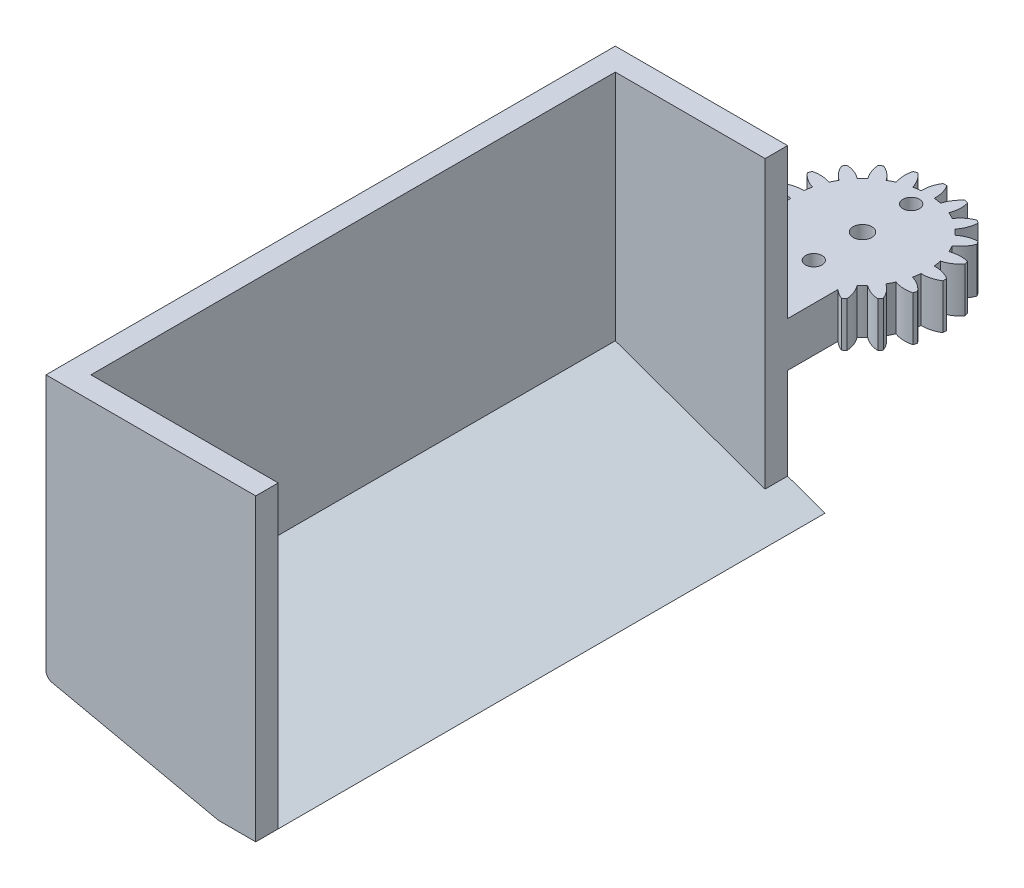
SolidWorks part; units mm, degrees
ref_plane "前视基准面" through (0, 0, 0) normal (0, 0, 1) x (1, 0, 0)
ref_plane "上视基准面" through (0, 0, 0) normal (0, 1, 0) x (1, 0, 0)
ref_plane "右视基准面" through (0, 0, 0) normal (1, 0, 0) x (0, 0, -1)
sketch "草图1" plane through (0, 0, 0) normal (0, 1, 0) x (1, 0, 0)
  line L0 (-5, 0) -> (5, 0) construction
  line L1 (5, 0) -> (5, -18)
  line L2 (-5, 0) -> (-5, -15)
  line L3 (-5, -15) -> (-18, -15)
  line L4 (-18, -15) -> (-18, -91)
  line L5 (-18, -91) -> (10, -91)
  line L6 (10, -91) -> (10, -88)
  line L7 (10, -88) -> (-15, -88)
  line L8 (-15, -88) -> (-15, -18)
  line L9 (-15, -18) -> (5, -18)
  arc A0 (5, 0) -> (-5, 0) centre (0, 0) ccw
  arc A1 (-5, 0) -> (5, 0) centre (0, 0) ccw construction
  circle A2 centre (0, 0) radius 1.25
  dimension "D1" = 10
  dimension "D2" = 3
  dimension "D3" = 3
  dimension "D4" = 3
  dimension "D5" = 10
  dimension "D6" = 15
  dimension "D7" = 25
  dimension "D8" = 70
extrude "凸台-拉伸1" add sketch "草图1" against normal blind 6
sketch "草图2" plane through (0, 0, 0) normal (0, 1, 0) x (1, 0, 0)
  line L0 (-15, -18) -> (5, -18) construction
  line L1 (-15, -88) -> (-15, -18) construction
  line L2 (10, -88) -> (-15, -88) construction
  line L3 (10, -91) -> (10, -88) construction
  line L4 (-18, -91) -> (10, -91) construction
  line L5 (-18, -15) -> (-18, -91) construction
  line L6 (-15, -18) -> (5, -18)
  line L7 (-15, -88) -> (-15, -18)
  line L8 (10, -88) -> (-15, -88)
  line L9 (10, -91) -> (10, -88)
  line L10 (-18, -91) -> (10, -91)
  line L11 (-18, -15) -> (-18, -91)
  line L12 (-18, -15) -> (5, -15)
  line L13 (5, -18) -> (5, 0) construction
  line L14 (5, -15) -> (5, -18)
extrude "凸台-拉伸2" add sketch "草图2" along normal mid plane 40
sketch "草图4" plane through (0, -6, 0) normal (0, -1, 0) x (1, 0, 0)
  circle A0 centre (0, 0) radius 1.25
  arc A80 (0.8607, 8.7066) -> (0.2434, 10.9973) centre (-3.1365, 8.858) ccw
  arc A81 (0.2434, 10.9973) -> (-0.2736, 10.9966) centre (0, 0) ccw
  arc A82 (-0.2736, 10.9966) -> (-0.8846, 8.7042) centre (3.1121, 8.8666) ccw
  arc A83 (-0.8846, 8.7042) -> (-1.8719, 8.5464) centre (0, 0) ccw
  arc A84 (-1.8719, 8.5464) -> (-3.1668, 10.5343) centre (-5.7202, 7.4553) ccw
  arc A85 (-3.1668, 10.5343) -> (-3.6584, 10.3738) centre (0, 0) ccw
  arc A86 (-3.6584, 10.3738) -> (-3.531, 8.0048) centre (0.2198, 9.3944) ccw
  arc A87 (-3.531, 8.0048) -> (-4.4213, 7.5497) centre (0, 0) ccw
  arc A88 (-4.4213, 7.5497) -> (-6.2671, 9.0401) centre (-7.7441, 5.3227) ccw
  arc A89 (-6.2671, 9.0401) -> (-6.685, 8.7356) centre (0, 0) ccw
  arc A90 (-6.685, 8.7356) -> (-5.8318, 6.5219) centre (-2.6939, 9.0025) ccw
  arc A91 (-5.8318, 6.5219) -> (-6.5379, 5.8139) centre (0, 0) ccw
  arc A92 (-6.5379, 5.8139) -> (-8.7539, 6.661) centre (-9.0099, 2.6692) ccw
  arc A93 (-8.7539, 6.661) -> (-9.0573, 6.2423) centre (0, 0) ccw
  arc A94 (-9.0573, 6.2423) -> (-7.5618, 4.4005) centre (-5.344, 7.7294) ccw
  arc A95 (-7.5618, 4.4005) -> (-8.0145, 3.509) centre (0, 0) ccw
  arc A96 (-8.0145, 3.509) -> (-10.3838, 3.6299) centre (-9.3937, -0.2457) ccw
  arc A97 (-10.3838, 3.6299) -> (-10.5429, 3.1379) centre (0, 0) ccw
  arc A98 (-10.5429, 3.1379) -> (-8.5515, 1.8484) centre (-7.471, 5.6997) ccw
  arc A99 (-8.5515, 1.8484) -> (-8.7066, 0.8607) centre (0, 0) ccw
  arc A100 (-8.7066, 0.8607) -> (-10.9973, 0.2434) centre (-8.858, -3.1365) ccw
  arc A101 (-10.9973, 0.2434) -> (-10.9966, -0.2736) centre (0, 0) ccw
  arc A102 (-10.9966, -0.2736) -> (-8.7042, -0.8846) centre (-8.8666, 3.1121) ccw
  arc A103 (-8.7042, -0.8846) -> (-8.5464, -1.8719) centre (0, 0) ccw
  arc A104 (-8.5464, -1.8719) -> (-10.5343, -3.1668) centre (-7.4553, -5.7202) ccw
  arc A105 (-10.5343, -3.1668) -> (-10.3738, -3.6584) centre (0, 0) ccw
  arc A106 (-10.3738, -3.6584) -> (-8.0048, -3.531) centre (-9.3944, 0.2198) ccw
  arc A107 (-8.0048, -3.531) -> (-7.5497, -4.4213) centre (0, 0) ccw
  arc A108 (-7.5497, -4.4213) -> (-9.0401, -6.2671) centre (-5.3227, -7.7441) ccw
  arc A109 (-9.0401, -6.2671) -> (-8.7356, -6.685) centre (0, 0) ccw
  arc A110 (-8.7356, -6.685) -> (-6.5219, -5.8318) centre (-9.0025, -2.6939) ccw
  arc A111 (-6.5219, -5.8318) -> (-5.8139, -6.5379) centre (0, 0) ccw
  arc A112 (-5.8139, -6.5379) -> (-6.661, -8.7539) centre (-2.6692, -9.0099) ccw
  arc A113 (-6.661, -8.7539) -> (-6.2423, -9.0573) centre (0, 0) ccw
  arc A114 (-6.2423, -9.0573) -> (-4.4005, -7.5618) centre (-7.7294, -5.344) ccw
  arc A115 (-4.4005, -7.5618) -> (-3.509, -8.0145) centre (0, 0) ccw
  arc A116 (-3.509, -8.0145) -> (-3.6299, -10.3838) centre (0.2457, -9.3937) ccw
  arc A117 (-3.6299, -10.3838) -> (-3.1379, -10.5429) centre (0, 0) ccw
  arc A118 (-3.1379, -10.5429) -> (-1.8484, -8.5515) centre (-5.6997, -7.471) ccw
  arc A119 (-1.8484, -8.5515) -> (-0.8607, -8.7066) centre (0, 0) ccw
  arc A120 (-0.8607, -8.7066) -> (-0.2434, -10.9973) centre (3.1365, -8.858) ccw
  arc A121 (-0.2434, -10.9973) -> (0.2736, -10.9966) centre (0, 0) ccw
  arc A122 (0.2736, -10.9966) -> (0.8846, -8.7042) centre (-3.1121, -8.8666) ccw
  arc A123 (0.8846, -8.7042) -> (1.8719, -8.5464) centre (0, 0) ccw
  arc A124 (1.8719, -8.5464) -> (3.1668, -10.5343) centre (5.7202, -7.4553) ccw
  arc A125 (3.1668, -10.5343) -> (3.6584, -10.3738) centre (0, 0) ccw
  arc A126 (3.6584, -10.3738) -> (3.531, -8.0048) centre (-0.2198, -9.3944) ccw
  arc A127 (3.531, -8.0048) -> (4.4213, -7.5497) centre (0, 0) ccw
  arc A128 (4.4213, -7.5497) -> (6.2671, -9.0401) centre (7.7441, -5.3227) ccw
  arc A129 (6.2671, -9.0401) -> (6.685, -8.7356) centre (0, 0) ccw
  arc A130 (6.685, -8.7356) -> (5.8318, -6.5219) centre (2.6939, -9.0025) ccw
  arc A131 (5.8318, -6.5219) -> (6.5379, -5.8139) centre (0, 0) ccw
  arc A132 (6.5379, -5.8139) -> (8.7539, -6.661) centre (9.0099, -2.6692) ccw
  arc A133 (8.7539, -6.661) -> (9.0573, -6.2423) centre (0, 0) ccw
  arc A134 (9.0573, -6.2423) -> (7.5618, -4.4005) centre (5.344, -7.7294) ccw
  arc A135 (7.5618, -4.4005) -> (8.0145, -3.509) centre (0, 0) ccw
  arc A136 (8.0145, -3.509) -> (10.3838, -3.6299) centre (9.3937, 0.2457) ccw
  arc A137 (10.3838, -3.6299) -> (10.5429, -3.1379) centre (0, 0) ccw
  arc A138 (10.5429, -3.1379) -> (8.5515, -1.8484) centre (7.471, -5.6997) ccw
  arc A139 (8.5515, -1.8484) -> (8.7066, -0.8607) centre (0, 0) ccw
  arc A140 (8.7066, -0.8607) -> (10.9973, -0.2434) centre (8.858, 3.1365) ccw
  arc A141 (10.9973, -0.2434) -> (10.9966, 0.2736) centre (0, 0) ccw
  arc A142 (10.9966, 0.2736) -> (8.7042, 0.8846) centre (8.8666, -3.1121) ccw
  arc A143 (8.7042, 0.8846) -> (8.5464, 1.8719) centre (0, 0) ccw
  arc A144 (8.5464, 1.8719) -> (10.5343, 3.1668) centre (7.4553, 5.7202) ccw
  arc A145 (10.5343, 3.1668) -> (10.3738, 3.6584) centre (0, 0) ccw
  arc A146 (10.3738, 3.6584) -> (8.0048, 3.531) centre (9.3944, -0.2198) ccw
  arc A147 (8.0048, 3.531) -> (7.5497, 4.4213) centre (0, 0) ccw
  arc A148 (7.5497, 4.4213) -> (9.0401, 6.2671) centre (5.3227, 7.7441) ccw
  arc A149 (9.0401, 6.2671) -> (8.7356, 6.685) centre (0, 0) ccw
  arc A150 (8.7356, 6.685) -> (6.5219, 5.8318) centre (9.0025, 2.6939) ccw
  arc A151 (6.5219, 5.8318) -> (5.8139, 6.5379) centre (0, 0) ccw
  arc A152 (5.8139, 6.5379) -> (6.661, 8.7539) centre (2.6692, 9.0099) ccw
  arc A153 (6.661, 8.7539) -> (6.2423, 9.0573) centre (0, 0) ccw
  arc A154 (6.2423, 9.0573) -> (4.4005, 7.5618) centre (7.7294, 5.344) ccw
  arc A155 (4.4005, 7.5618) -> (3.509, 8.0145) centre (0, 0) ccw
  arc A156 (3.509, 8.0145) -> (3.6299, 10.3838) centre (-0.2457, 9.3937) ccw
  arc A157 (3.6299, 10.3838) -> (3.1379, 10.5429) centre (0, 0) ccw
  arc A158 (3.1379, 10.5429) -> (1.8484, 8.5515) centre (5.6997, 7.471) ccw
  arc A159 (1.8484, 8.5515) -> (0.8607, 8.7066) centre (0, 0) ccw
  arc A160 (0.8607, 8.7066) -> (0.2434, 10.9973) centre (-3.1365, 8.858) ccw
  arc A161 (0.2434, 10.9973) -> (-0.2736, 10.9966) centre (0, 0) ccw
  arc A162 (-0.2736, 10.9966) -> (-0.8846, 8.7042) centre (3.1121, 8.8666) ccw
  arc A163 (-0.8846, 8.7042) -> (-1.8719, 8.5464) centre (0, 0) ccw
  arc A164 (-1.8719, 8.5464) -> (-3.1668, 10.5343) centre (-5.7202, 7.4553) ccw
  arc A165 (-3.1668, 10.5343) -> (-3.6584, 10.3738) centre (0, 0) ccw
  arc A166 (-3.6584, 10.3738) -> (-3.531, 8.0048) centre (0.2198, 9.3944) ccw
  arc A167 (-3.531, 8.0048) -> (-4.4213, 7.5497) centre (0, 0) ccw
  arc A168 (-4.4213, 7.5497) -> (-6.2671, 9.0401) centre (-7.7441, 5.3227) ccw
  arc A169 (-6.2671, 9.0401) -> (-6.685, 8.7356) centre (0, 0) ccw
  arc A170 (-6.685, 8.7356) -> (-5.8318, 6.5219) centre (-2.6939, 9.0025) ccw
  arc A171 (-5.8318, 6.5219) -> (-6.5379, 5.8139) centre (0, 0) ccw
  arc A172 (-6.5379, 5.8139) -> (-8.7539, 6.661) centre (-9.0099, 2.6692) ccw
  arc A173 (-8.7539, 6.661) -> (-9.0573, 6.2423) centre (0, 0) ccw
  arc A174 (-9.0573, 6.2423) -> (-7.5618, 4.4005) centre (-5.344, 7.7294) ccw
  arc A175 (-7.5618, 4.4005) -> (-8.0145, 3.509) centre (0, 0) ccw
  arc A176 (-8.0145, 3.509) -> (-10.3838, 3.6299) centre (-9.3937, -0.2457) ccw
  arc A177 (-10.3838, 3.6299) -> (-10.5429, 3.1379) centre (0, 0) ccw
  arc A178 (-10.5429, 3.1379) -> (-8.5515, 1.8484) centre (-7.471, 5.6997) ccw
  arc A179 (-8.5515, 1.8484) -> (-8.7066, 0.8607) centre (0, 0) ccw
  arc A180 (-8.7066, 0.8607) -> (-10.9973, 0.2434) centre (-8.858, -3.1365) ccw
  arc A181 (-10.9973, 0.2434) -> (-10.9966, -0.2736) centre (0, 0) ccw
  arc A182 (-10.9966, -0.2736) -> (-8.7042, -0.8846) centre (-8.8666, 3.1121) ccw
  arc A183 (-8.7042, -0.8846) -> (-8.5464, -1.8719) centre (0, 0) ccw
  arc A184 (-8.5464, -1.8719) -> (-10.5343, -3.1668) centre (-7.4553, -5.7202) ccw
  arc A185 (-10.5343, -3.1668) -> (-10.3738, -3.6584) centre (0, 0) ccw
  arc A186 (-10.3738, -3.6584) -> (-8.0048, -3.531) centre (-9.3944, 0.2198) ccw
  arc A187 (-8.0048, -3.531) -> (-7.5497, -4.4213) centre (0, 0) ccw
  arc A188 (-7.5497, -4.4213) -> (-9.0401, -6.2671) centre (-5.3227, -7.7441) ccw
  arc A189 (-9.0401, -6.2671) -> (-8.7356, -6.685) centre (0, 0) ccw
  arc A190 (-8.7356, -6.685) -> (-6.5219, -5.8318) centre (-9.0025, -2.6939) ccw
  arc A191 (-6.5219, -5.8318) -> (-5.8139, -6.5379) centre (0, 0) ccw
  arc A192 (-5.8139, -6.5379) -> (-6.661, -8.7539) centre (-2.6692, -9.0099) ccw
  arc A193 (-6.661, -8.7539) -> (-6.2423, -9.0573) centre (0, 0) ccw
  arc A194 (-6.2423, -9.0573) -> (-4.4005, -7.5618) centre (-7.7294, -5.344) ccw
  arc A195 (-4.4005, -7.5618) -> (-3.509, -8.0145) centre (0, 0) ccw
  arc A196 (-3.509, -8.0145) -> (-3.6299, -10.3838) centre (0.2457, -9.3937) ccw
  arc A197 (-3.6299, -10.3838) -> (-3.1379, -10.5429) centre (0, 0) ccw
  arc A198 (-3.1379, -10.5429) -> (-1.8484, -8.5515) centre (-5.6997, -7.471) ccw
  arc A199 (-1.8484, -8.5515) -> (-0.8607, -8.7066) centre (0, 0) ccw
  arc A200 (-0.8607, -8.7066) -> (-0.2434, -10.9973) centre (3.1365, -8.858) ccw
  arc A201 (-0.2434, -10.9973) -> (0.2736, -10.9966) centre (0, 0) ccw
  arc A202 (0.2736, -10.9966) -> (0.8846, -8.7042) centre (-3.1121, -8.8666) ccw
  arc A203 (0.8846, -8.7042) -> (1.8719, -8.5464) centre (0, 0) ccw
  arc A204 (1.8719, -8.5464) -> (3.1668, -10.5343) centre (5.7202, -7.4553) ccw
  arc A205 (3.1668, -10.5343) -> (3.6584, -10.3738) centre (0, 0) ccw
  arc A206 (3.6584, -10.3738) -> (3.531, -8.0048) centre (-0.2198, -9.3944) ccw
  arc A207 (3.531, -8.0048) -> (4.4213, -7.5497) centre (0, 0) ccw
  arc A208 (4.4213, -7.5497) -> (6.2671, -9.0401) centre (7.7441, -5.3227) ccw
  arc A209 (6.2671, -9.0401) -> (6.685, -8.7356) centre (0, 0) ccw
  arc A210 (6.685, -8.7356) -> (5.8318, -6.5219) centre (2.6939, -9.0025) ccw
  arc A211 (5.8318, -6.5219) -> (6.5379, -5.8139) centre (0, 0) ccw
  arc A212 (6.5379, -5.8139) -> (8.7539, -6.661) centre (9.0099, -2.6692) ccw
  arc A213 (8.7539, -6.661) -> (9.0573, -6.2423) centre (0, 0) ccw
  arc A214 (9.0573, -6.2423) -> (7.5618, -4.4005) centre (5.344, -7.7294) ccw
  arc A215 (7.5618, -4.4005) -> (8.0145, -3.509) centre (0, 0) ccw
  arc A216 (8.0145, -3.509) -> (10.3838, -3.6299) centre (9.3937, 0.2457) ccw
  arc A217 (10.3838, -3.6299) -> (10.5429, -3.1379) centre (0, 0) ccw
  arc A218 (10.5429, -3.1379) -> (8.5515, -1.8484) centre (7.471, -5.6997) ccw
  arc A219 (8.5515, -1.8484) -> (8.7066, -0.8607) centre (0, 0) ccw
  arc A220 (8.7066, -0.8607) -> (10.9973, -0.2434) centre (8.858, 3.1365) ccw
  arc A221 (10.9973, -0.2434) -> (10.9966, 0.2736) centre (0, 0) ccw
  arc A222 (10.9966, 0.2736) -> (8.7042, 0.8846) centre (8.8666, -3.1121) ccw
  arc A223 (8.7042, 0.8846) -> (8.5464, 1.8719) centre (0, 0) ccw
  arc A224 (8.5464, 1.8719) -> (10.5343, 3.1668) centre (7.4553, 5.7202) ccw
  arc A225 (10.5343, 3.1668) -> (10.3738, 3.6584) centre (0, 0) ccw
  arc A226 (10.3738, 3.6584) -> (8.0048, 3.531) centre (9.3944, -0.2198) ccw
  arc A227 (8.0048, 3.531) -> (7.5497, 4.4213) centre (0, 0) ccw
  arc A228 (7.5497, 4.4213) -> (9.0401, 6.2671) centre (5.3227, 7.7441) ccw
  arc A229 (9.0401, 6.2671) -> (8.7356, 6.685) centre (0, 0) ccw
  arc A230 (8.7356, 6.685) -> (6.5219, 5.8318) centre (9.0025, 2.6939) ccw
  arc A231 (6.5219, 5.8318) -> (5.8139, 6.5379) centre (0, 0) ccw
  arc A232 (5.8139, 6.5379) -> (6.661, 8.7539) centre (2.6692, 9.0099) ccw
  arc A233 (6.661, 8.7539) -> (6.2423, 9.0573) centre (0, 0) ccw
  arc A234 (6.2423, 9.0573) -> (4.4005, 7.5618) centre (7.7294, 5.344) ccw
  arc A235 (4.4005, 7.5618) -> (3.509, 8.0145) centre (0, 0) ccw
  arc A236 (3.509, 8.0145) -> (3.6299, 10.3838) centre (-0.2457, 9.3937) ccw
  arc A237 (3.6299, 10.3838) -> (3.1379, 10.5429) centre (0, 0) ccw
  arc A238 (3.1379, 10.5429) -> (1.8484, 8.5515) centre (5.6997, 7.471) ccw
  arc A239 (1.8484, 8.5515) -> (0.8607, 8.7066) centre (0, 0) ccw
  point P0 (0, 0)
  dimension "D1" = 0
extrude "凸台-拉伸4" add sketch "草图4" against normal blind 6
sketch "草图5" plane through (0, -6, 0) normal (0, -1, 0) x (1, 0, 0)
  line L0 (0, -6.5) -> (0, 6.5) construction
  circle A0 centre (0, 6.5) radius 1.1
  circle A1 centre (0, -6.5) radius 1.1
  point P4 (0, 0)
  dimension "D2" = 2.2
  dimension "D3" = 2.2
  dimension "D1" = 13
extrude "切除-拉伸1" cut sketch "草图5" against normal through all
sketch "草图6" plane through (0, 0, 91) normal (0, 0, 1) x (1, 0, 0)
  line L2 (-18, -20) -> (-18, 20) construction
  line L3 (-18, -10) -> (10, -20)
  line L5 (-18, -10) -> (-18, -20)
  line L6 (-18, -20) -> (10, -20)
extrude "凸台-拉伸5" add sketch "草图6" against normal blind 76
sketch "草图8" plane through (0, 0, 91) normal (0, 0, 1) x (1, 0, 0)
  line L0 (-17.2124, -15.1712) -> (4.895, -19.9772)
  line L1 (-18, -20) -> (-18, 20) construction
  line L2 (-18, -20) -> (10, -20) construction
  line L3 (5.1074, -20) -> (5.1074, -20.3068)
  line L6 (5.1074, -20.3068) -> (-18, -20.3068)
  line L7 (-18, -14.194) -> (-18, -19.9772)
  line L9 (-18, -20.3068) -> (-18, -19.9772)
  arc A0 (-17.2124, -15.1712) -> (-18, -14.194) centre (-17, -14.194) cw
  arc A1 (5.1074, -20) -> (4.895, -19.9772) centre (5.1074, -19) cw
  point P13 (-18, -15)
  point P16 (5, -20)
  dimension "D1" = 1
  dimension "D2" = 1
extrude "切除-拉伸2" cut sketch "草图8" against normal blind 76
